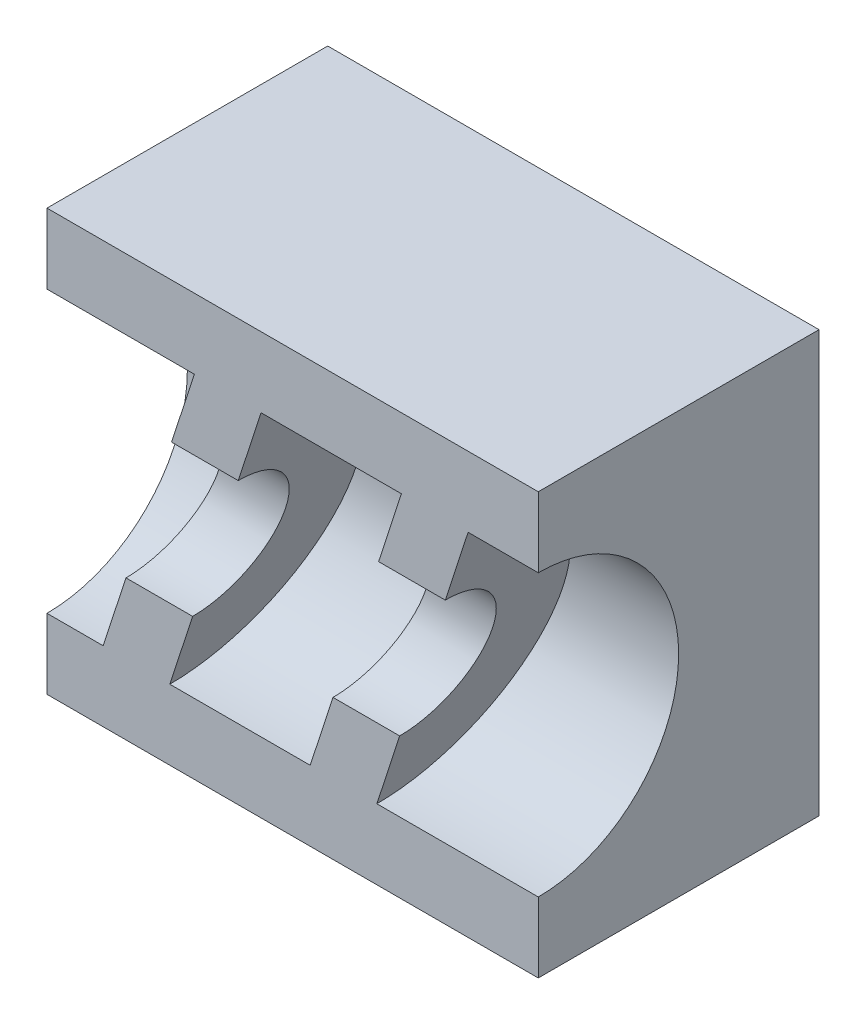
SolidWorks part; units mm, degrees
ref_plane "前视基准面" through (0, 0, 0) normal (0, 0, 1) x (1, 0, 0)
ref_plane "上视基准面" through (0, 0, 0) normal (0, 1, 0) x (1, 0, 0)
ref_plane "右视基准面" through (0, 0, 0) normal (1, 0, 0) x (0, 0, -1)
other "Configuration Table"
sketch "草图1" plane through (0, 0, 0) normal (0, 0, 1) x (1, 0, 0)
  line L1 (0, 0) -> (7, 0)
  line L2 (0, 0) -> (0, 6)
  line L3 (0, 6) -> (7, 6)
  line L4 (7, 0) -> (7, 6)
  dimension "D1" = 7
  dimension "D2" = 6
extrude "凸台-拉伸1" add sketch "草图1" along normal blind 4
sketch "草图2" plane through (0, 0, 0) normal (-1, 0, 0) x (0, 0, 1)
  line L0 (4, 6) -> (4, 0) construction
  circle A0 centre (4, 3) radius 2
  point P4 (4, 3)
  dimension "D1" = 4
extrude "切除-拉伸1" cut sketch "草图2" against normal through all
sketch "草图6" plane through (0, 0, 4) normal (0, 0, 1) x (1, 0, 0)
  line L0 (5.05, 5) -> (6, 5)
  line L1 (5.05, 5) -> (3.7503, 1)
  line L2 (6, 5) -> (4.7003, 1)
  line L3 (3.7503, 1) -> (4.7003, 1)
  line L4 (0, 5) -> (7, 5) construction
  line L5 (7, 1) -> (0, 1) construction
  line L6 (2.1, 5) -> (3.05, 5)
  line L7 (2.1, 5) -> (0.8003, 1)
  line L8 (3.05, 5) -> (1.7503, 1)
  line L9 (0.8003, 1) -> (1.7503, 1)
  dimension "D1" = 0.95
  dimension "D2" = 0.95
  dimension "D3" = 2
  dimension "D4" = 1
  dimension "D5" = 72
  dimension "D6" = 72
extrude "凸台-拉伸2" add sketch "草图6" against normal through all
sketch "草图7" plane through (7, 0, 0) normal (1, 0, 0) x (0, 0, -1)
  circle A0 centre (-4, 3) radius 1
  arc A1 (-4, 1) -> (-4, 5) centre (-4, 3) ccw construction
  dimension "D1" = 2
extrude "切除-拉伸3" cut sketch "草图7" against normal through all
